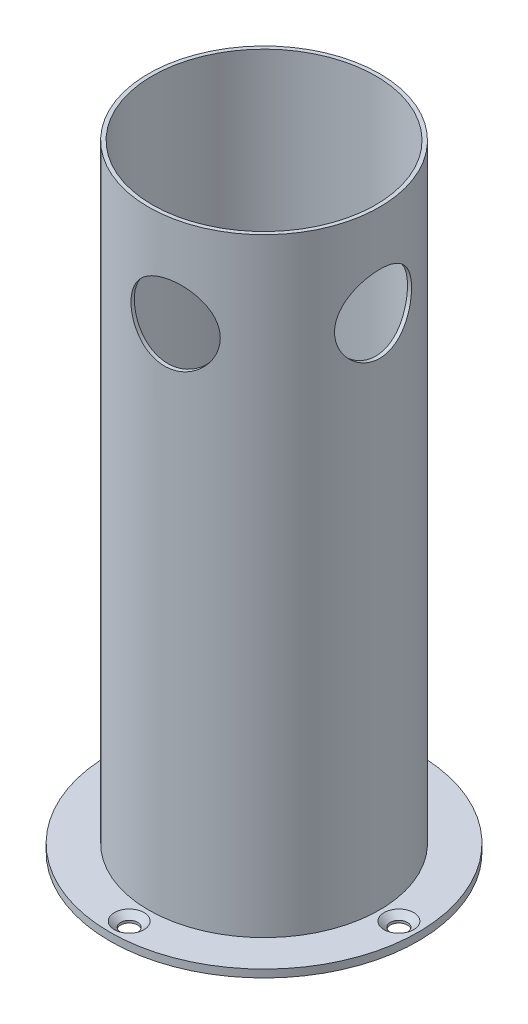
SolidWorks part; units mm, degrees
material "AISI 316 Stainless Steel Sheet (SS)"
ref_plane "Front Plane" through (0, 0, 0) normal (0, 0, 1) x (1, 0, 0)
ref_plane "Top Plane" through (0, 0, 0) normal (0, 1, 0) x (1, 0, 0)
ref_plane "Right Plane" through (0, 0, 0) normal (1, 0, 0) x (0, 0, -1)
sketch "Sketch1" plane through (0, 0, 0) normal (0, 1, 0) x (1, 0, 0)
  circle A0 centre (0, 0) radius 38.1
  circle A1 centre (0, 0) radius 36.83
  dimension "D1" = 76.2
  dimension "D2" = 73.66
extrude "Boss-Extrude1" add sketch "Sketch1" along normal blind 203.2
sketch "Sketch2" plane through (0, 0, 0) normal (1, 0, 0) x (0, 0, -1)
  line L0 (36.83, 203.2) -> (-36.83, 203.2) construction
  circle A0 centre (0, 172.72) radius 12.7
  dimension "D1" = 25.4
  dimension "D2" = 30.48
extrude "Cut-Extrude1" cut sketch "Sketch2" along normal through all
sketch "Sketch3" plane through (0, 0, 0) normal (1, 0, 0) x (0, 0, -1)
  line L0 (0, 0) -> (0, 216.1345) construction
pattern_circular "CirPattern2" count 2 every 80 about axis through (0, 203.2, 0) along (0, -1, 0) of "Cut-Extrude1"
sketch "Sketch5" plane through (0, 0, 0) normal (0, 1, 0) x (1, 0, 0)
  circle A0 centre (0, 0) radius 50.8
  circle A1 centre (0, 0) radius 38.1 construction
  circle A2 centre (0, 0) radius 38.1
  dimension "D1" = 101.6
extrude "Boss-Extrude2" add sketch "Sketch5" along normal blind 2.54
hole_wizard "CSK for #10 Flat Head Machine Screw (100)1" positions "Sketch6" profile "Sketch7" countersink size "#10" standard "ANSI Inch" end condition through all
sketch "Sketch6" plane through (0, 2.54, 0) normal (0, 1, 0) x (1, 0, 0)
  line L0 (0, 0) -> (0, 67.4984) construction
  line L1 (0, 0) -> (68.7256, 0) construction
  point P8 (44.45, 0)
  point P10 (0, 44.45)
  dimension "D1" = 44.45
  dimension "D2" = 44.45
sketch "Sketch7" plane through (0, 2.54, -44.45) normal (1, 0, 0) x (0, 0, 1)
  line L0 (0, 0) -> (0, 2.54)
  line L1 (0, 2.54) -> (2.8067, 2.54)
  line L2 (2.8067, 2.54) -> (2.8067, 1.7477)
  line L3 (2.8067, 1.7477) -> (4.8895, 0)
  line L5 (4.8895, 0) -> (0, 0)
  line L6 (-2.8067, 1.7477) -> (-4.8895, 0) construction
  line L11 (0, -6.35) -> (0, 107.95) construction
  dimension "Thru Hole Dia." = 5.6134
  dimension "Thru Hole Depth" = 2.54
  dimension "Near C'Sink Dia." = 9.779
  dimension "Near C'Sink Angle" = 100
pattern_circular "CirPattern3" count 2 every 180 about axis through (0, 0, 0) along (0, 1, 0) of "CSK for #10 Flat Head Machine Screw (100)1"
